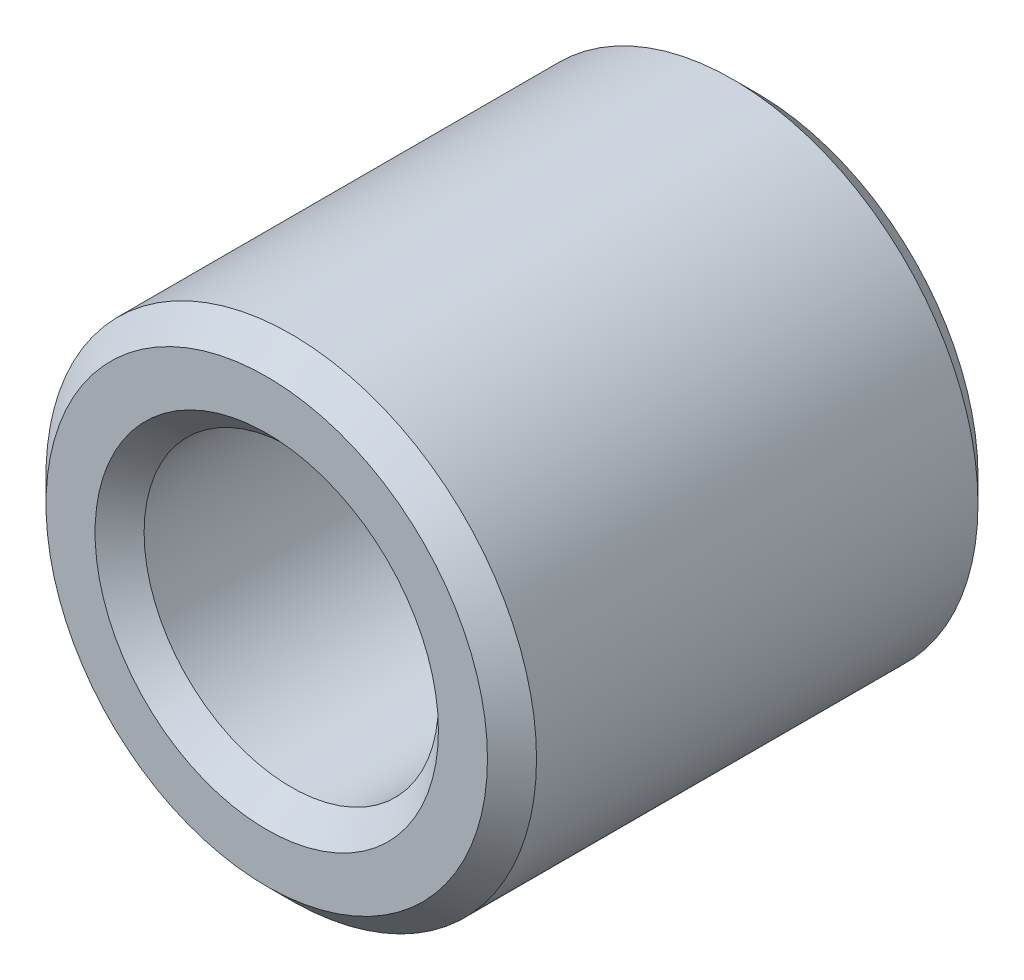
SolidWorks part; units mm, degrees
material "Tin Bearing Bronze"
ref_plane "Front Plane" through (0, 0, 0) normal (0, 0, 1) x (1, 0, 0)
ref_plane "Top Plane" through (0, 0, 0) normal (0, 1, 0) x (1, 0, 0)
ref_plane "Right Plane" through (0, 0, 0) normal (1, 0, 0) x (0, 0, -1)
sketch "Sketch1" plane through (0, 0, 0) normal (0, 0, 1) x (1, 0, 0)
  circle A0 centre (0, 0) radius 3
  circle A1 centre (0, 0) radius 5
  dimension "D1" = 6
  dimension "D2" = 10
extrude "Boss-Extrude1" add sketch "Sketch1" along normal blind 10
chamfer "Chamfer1" distance 0.5 angle 45 4 edges at (5, 0, 0) (3, 0, 0) (3, 0, 10) (5, 0, 10)
